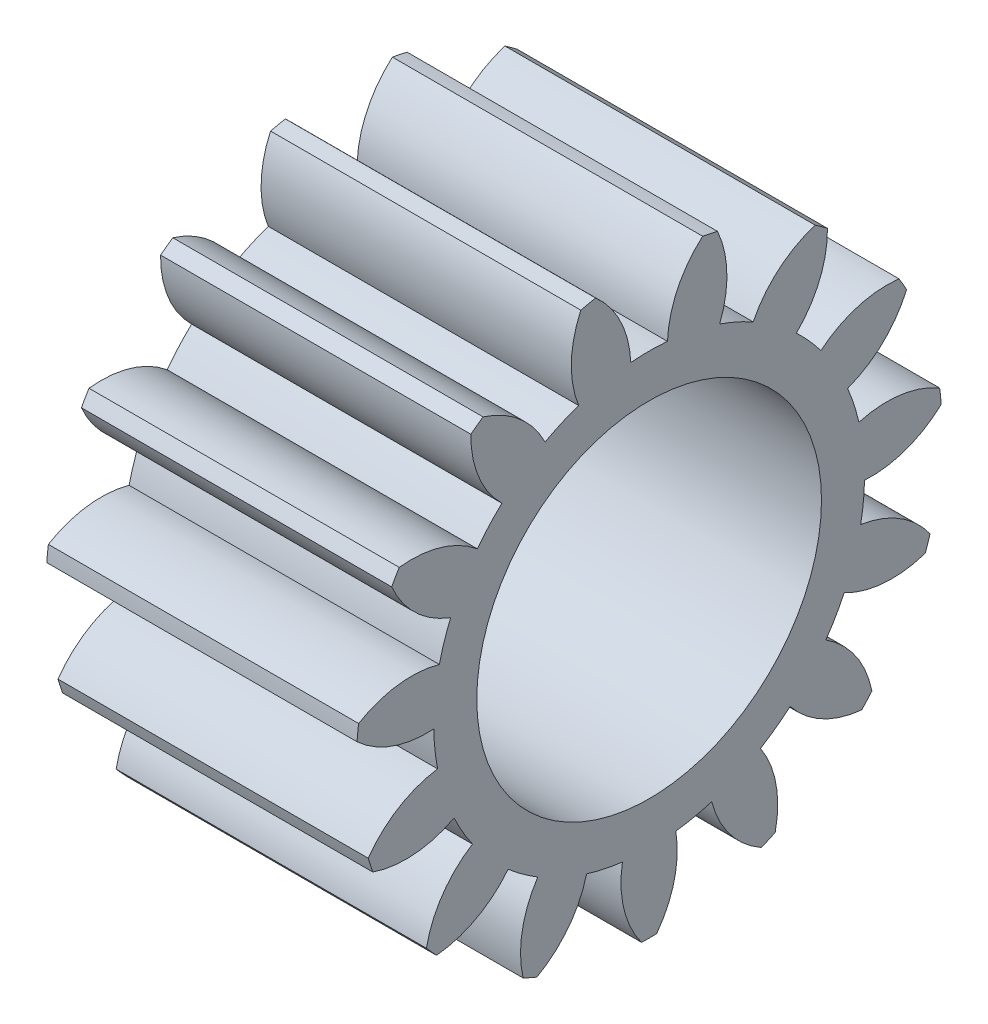
SolidWorks part; units mm, degrees
ref_plane "Plane1" through (0, 0, 0) normal (0, 0, 1) x (1, 0, 0)
ref_plane "Plane2" through (0, 0, 0) normal (0, 1, 0) x (1, 0, 0)
ref_plane "Plane3" through (0, 0, 0) normal (1, 0, 0) x (0, 0, -1)
other "Configuration Table"
sketch "HoldingSke" plane through (0, 0, 0) normal (0, 1, 0) x (1, 0, 0)
  line L0 (0, 0) -> (0.9659, -0.2588)
  line L1 (-15, 0) -> (100, 0) construction
  line L2 (0, 0) -> (-2.1039, 2.3779)
  line L3 (0, 0) -> (-11.863, 4.5341)
  line L4 (0, 0) -> (8.3417, 2.2352)
  line L5 (0, 0) -> (-46.8476, -17.4728)
  line L6 (0, 0) -> (-7.4607, -5.0337)
  line L7 (-2.1039, 2.3779) -> (8.6586, 51.2059)
  line L8 (-76.2, 54.61) -> (-75.2, 54.61)
  line L9 (-71.009, 38.7566) -> (-53.1078, 45.2721)
  line L10 (-76.2, 71.12) -> (104.1128, 71.12)
  line L11 (0, 0) -> (-9, 0)
  line L12 (-76.2, 101.6) -> (-76.162, 101.6)
  line L13 (24.9733, 27.94) -> (52.9518, 28.4284)
  line L14 (24.9733, 27.94) -> (24.9743, 27.94)
  line L15 (24.9733, 27.94) -> (100.4006, 29.5858)
  line L16 (-63.627, -1) -> (-12.827, -1)
  circle A0 centre (0, 0) radius 3
  circle A1 centre (0, 0) radius 6.249
  circle A2 centre (0, 0) radius 37.5
  circle A3 centre (0, 0) radius 3
  dimension "MHD" = 12.498
  dimension "Hub_dia" = 75
  dimension "Bore" = 6
  dimension "MBD" = 6
  dimension "Num_teeth" = 15
  dimension "Pitch" = 1
  dimension "Overall_len" = 50
  dimension "Show_teeth" = 15
  dimension "Thickness" = 9
  dimension "OAL" = 50.0001
  dimension "T_dim" = 1
  dimension "Ap" = 20
  dimension "H" = 19.05
  dimension "Pitch_radius" = 180.3128
  dimension "Width" = 9
  dimension "Backlash" = 0.038
  dimension "Addendum_fac" = 1
  dimension "Dedendum_fac" = 1.25
  dimension "Clearance_fac" = 0.25
  dimension "Dedendum_add" = 0.001
  dimension "Module" = 1
sketch "BasProSke" plane through (0, 0, 0) normal (0, 1, 0) x (1, 0, 0)
  line L0 (-10, 0) -> (60, 0) construction
  line L1 (0, 0) -> (0, 8.5)
  line L2 (0, 0) -> (9, 0)
  line L3 (9, 0) -> (9, 8.5)
  line L4 (9, 8.5) -> (0, 8.5)
  dimension "Thickness" = 9
  dimension "Diameter" = 17
revolve "Base-Revolve" add sketch "BasProSke" angle 360 about L0
sketch "TooCutSke" plane through (0, 0, 0) normal (1, 0, 0) x (0, 0, -1)
  line L1 (0, 0) -> (0, 107) construction
  line L2 (0, 0) -> (-0.8504, 7.4516) construction
  line L3 (0, 0) -> (-3.1044, 14.6049) construction
  line L4 (-0.8504, 7.4516) -> (-1.5522, 7.3025) construction
  arc A0 (0.5316, 6.2263) -> (-0.5316, 6.2263) centre (0, 0) ccw
  arc A1 (1.5766, 8.3784) -> (-1.5766, 8.3784) centre (0, 0) ccw
  circle A2 centre (0, 0) radius 7.5 construction
  circle A3 centre (0, 0) radius 7.0477 construction
  arc A4 (-0.5316, 6.2263) -> (-1.5766, 8.3784) centre (-3.5289, 6.1005) ccw
  arc A5 (1.5766, 8.3784) -> (0.5316, 6.2263) centre (3.5289, 6.1005) ccw
  dimension "Root_dia" = 12.498
  dimension "Overcut_dia" = 17.0508
  dimension "Pitch_dia" = 15
  dimension "Base_dia" = 14.0954
  dimension "Flank_rad" = 3
  dimension "Half_ang" = 12
  dimension "Half_CT" = 0.7175
extrude "ToothCut" cut sketch "TooCutSke" along normal through all
fillet "Breaks" [suppressed] radius 0.02
fillet "RootFillets" [suppressed] radius 0.251
pattern_circular "TeethCuts" count 15 every 24 about axis through (-10, 0, 0) along (1, 0, 0) of "ToothCut", "RootFillets", "Breaks"
sketch "HubNeaOneSke" plane through (0, 0, 0) normal (-1, 0, 0) x (0, 0, 1)
  circle A0 centre (0, 0) radius 6.249
  dimension "Diameter" = 12.498
extrude "HubNearOne" [suppressed] add sketch "HubNeaOneSke" along normal blind 41.0001
sketch "HubNeaBotSke" plane through (0, 0, 0) normal (-1, 0, 0) x (0, 0, 1)
  circle A0 centre (0, 0) radius 6.249
  dimension "Diameter" = 12.498
extrude "HubNearBoth" [suppressed] add sketch "HubNeaBotSke" along normal blind 20.5
ref_plane "FarPln" through (9, 0, 0) normal (1, 0, 0) x (0, 0, -1)
sketch "HubFarSke" plane through (9, 0, 0) normal (1, 0, 0) x (0, 0, -1)
  circle A0 centre (0, 0) radius 6.249
  dimension "Diameter" = 12.498
extrude "HubFar" [suppressed] add sketch "HubFarSke" along normal blind 20.5
sketch "BorSke" plane through (0, 0, 0) normal (1, 0, 0) x (0, 0, -1)
  circle A0 centre (0, 0) radius 3
  dimension "Diameter" = 6
extrude "Bore" cut sketch "BorSke" along normal mid plane 100.0001
sketch "KeySke" plane through (0, 0, 0) normal (1, 0, 0) x (0, 0, -1)
  line L0 (-1, 0) -> (-1, 4)
  line L1 (-1, 4) -> (1, 4)
  line L2 (1, 4) -> (1, 0)
  line L3 (0, 0) -> (0, 34) construction
  line L4 (-1, 0) -> (1, 0)
  dimension "Offset" = 4
  dimension "Width" = 2
extrude "Keyway" [suppressed] cut sketch "KeySke" along normal mid plane 100.0001
pattern_circular "Keyway2" [suppressed] count 2 every 90 about axis through (-10, 0, 0) along (1, 0, 0)
sketch "Sketch1" plane through (9, 0, 0) normal (1, 0, 0) x (0, 0, -1)
  circle A0 centre (0, 0) radius 5
  dimension "D1" = 10
extrude "Cut-Extrude1" cut sketch "Sketch1" against normal up to surface (9 mm away) up to face at (0, 0, -3)
equation "' \"Module@HoldingSke\" = 6.35"
equation "' \"Num_teeth@HoldingSke\" = 12"
equation "' \"Ap@HoldingSke\" =  20"
equation "' \"Ap@HoldingSke\" = 20"
equation "' \"Width@HoldingSke\" = 0.5 * 25.4"
equation "' \"Hub_dia@HoldingSke\"= 1 * 25.4"
equation "' \"Hub_dia@HoldingSke\" = 1 * 25.4"
equation "' \"Overall_len@HoldingSke\" = 1.0 * 25.4"
equation "' \"Bore@HoldingSke\" = 0.75 * 25.4"
equation "' \"T_dim@HoldingSke\" = 0.1 * 25.4"
equation "' \"Width@KeySke\" = 0.25 * 25.4"
equation "' \"Show_teeth@HoldingSke\" = 13"
equation "' \"Backlash@HoldingSke\" = 0.009 * 25.4"
equation "' \"Addendum_fac@HoldingSke\" = 1.0"
equation "' \"Dedendum_fac@HoldingSke\" = 1.25"
equation "' \"Dedendum_add@HoldingSke\" = 0.00005 * 25.4"
equation "' \"Clearance_fac@HoldingSke\" = 0.25"
equation "\"Pitch@HoldingSke\" = 1 / \"Module@HoldingSke\""
equation "\"Overcut_dia@TooCutSke\" = (\"Num_teeth@HoldingSke\" + 2 * \"Addendum_fac@HoldingSke\") / \"Pitch@HoldingSke\" + 0.002 * 25.4"
equation "\"Pitch_dia@TooCutSke\" = \"Num_teeth@HoldingSke\" / \"Pitch@HoldingSke\""
equation "\"Base_dia@TooCutSke\" = \"Num_teeth@HoldingSke\" / \"Pitch@HoldingSke\" * cos((\"Ap@HoldingSke\"  * 3.14159265 / 180))"
equation "\"Root_dia@TooCutSke\" = (\"Num_teeth@HoldingSke\" + 2) / \"Pitch@HoldingSke\" - 2 * (\"Addendum_fac@HoldingSke\" + \"Dedendum_fac@HoldingSke\") / \"Pitch@HoldingSke\" - \"Dedendum_add@HoldingSke\" * 2"
equation "\"Half_ang@TooCutSke\" = 180 / \"Num_teeth@HoldingSke\""
equation "\"Half_CT@TooCutSke\" = \"Num_teeth@HoldingSke\" / \"Pitch@HoldingSke\" * sin((3.14159265 / 2 / \"Num_teeth@HoldingSke\")) / 2 - 7 * \"Backlash@HoldingSke\" / 4"
equation "\"Flank_rad@TooCutSke\" = \"Num_teeth@HoldingSke\" / \"Pitch@HoldingSke\" / 5"
equation "\"Radius@RootFillets\" = \"Clearance_fac@HoldingSke\" / \"Pitch@HoldingSke\" + \"Dedendum_add@HoldingSke\""
equation "\"Break_rad@Breaks\" = 0.02 / \"Pitch@HoldingSke\""
equation "\"Thickness@HoldingSke\" = \"Width@HoldingSke\""
equation "\"OAL@HoldingSke\" = \"Thickness@HoldingSke\""
equation "\"MHD@HoldingSke\" = (\"Num_teeth@HoldingSke\" + 2) / \"Pitch@HoldingSke\" - 2 * (\"Addendum_fac@HoldingSke\" + \"Dedendum_fac@HoldingSke\")  / \"Pitch@HoldingSke\" - \"Dedendum_add@HoldingSke\" * 2"
equation "\"MBD@HoldingSke\" = (\"Num_teeth@HoldingSke\" + 2) / \"Pitch@HoldingSke\" - 2 * (\"Addendum_fac@HoldingSke\" + \"Dedendum_fac@HoldingSke\")  / \"Pitch@HoldingSke\" - \"Dedendum_add@HoldingSke\" * 2 - 0.002 * 25.4"
equation "\"MHD@HoldingSke\" = ((sgn( \"MHD@HoldingSke\" - \"Hub_dia@HoldingSke\" )-1)*( \"MHD@HoldingSke\" - \"Hub_dia@HoldingSke\" ))/-2+ \"Hub_dia@HoldingSke\""
equation "\"MBD@HoldingSke\" = ((sgn( \"MBD@HoldingSke\" - \"Bore@HoldingSke\" )-1)*( \"MBD@HoldingSke\" - \"Bore@HoldingSke\" ))/-2+ \"Bore@HoldingSke\""
equation "\"OAL@HoldingSke\" = ((sgn( \"OAL@HoldingSke\" - \"Overall_len@HoldingSke\" )+1)*( \"OAL@HoldingSke\" - \"Overall_len@HoldingSke\" ))/2 + \"Overall_len@HoldingSke\" + 0.000002 * 25.4"
equation "\"Num_teeth@TeethCuts\" = int( \"Show_teeth@HoldingSke\" ) + 1"
equation "\"Num_teeth@TeethCuts\" = ((sgn( \"Num_teeth@TeethCuts\" - \"Num_teeth@HoldingSke\" )-1)*( \"Num_teeth@TeethCuts\" - \"Num_teeth@HoldingSke\" ))/-2+ \"Num_teeth@HoldingSke\""
equation "\"Num_teeth@TeethCuts\" = ((sgn( \"Num_teeth@TeethCuts\" - 2.0)+1)*( \"Num_teeth@TeethCuts\" - 2.0))/2 +2.0"
equation "\"Angle@TeethCuts\" = 360.0 / \"Num_teeth@HoldingSke\""
equation "\"Diameter@BasProSke\" = (\"Num_teeth@HoldingSke\" + 2 * \"Addendum_fac@HoldingSke\") / \"Pitch@HoldingSke\""
equation "\"Thickness@BasProSke\"  = \"Thickness@HoldingSke\""
equation "' \"Fillet_rad@BasProSke\" =  \"Thickness@HoldingSke\" * 0.05"
equation "' \"Fillet_rad@BasProSke\" = \"Thickness@HoldingSke\" * 0.05"
equation "\"MHD@HoldingSke\" = ((sgn( \"MHD@HoldingSke\" - \"Root_dia@TooCutSke\" )-1)*( \"MHD@HoldingSke\" - \"Root_dia@TooCutSke\" ))/-2+ \"Root_dia@TooCutSke\""
equation "\"Diameter@HubNeaOneSke\" = \"MHD@HoldingSke\""
equation "\"Length@HubNearOne\" = \"OAL@HoldingSke\" - \"Thickness@BasProSke\""
equation "\"Diameter@HubNeaBotSke\" = \"MHD@HoldingSke\""
equation "\"Length@HubNearBoth\" = ( \"OAL@HoldingSke\" - \"Thickness@BasProSke\" ) / 2.0"
equation "\"Thickness@FarPln\" = \"Thickness@BasProSke\""
equation "\"Diameter@HubFarSke\" = \"MHD@HoldingSke\""
equation "\"Length@HubFar\" = ( \"OAL@HoldingSke\" - \"Thickness@BasProSke\" ) / 2.0"
equation "\"Diameter@BorSke\" = \"MBD@HoldingSke\""
equation "\"D1@Bore\" = \"OAL@HoldingSke\" * 2.0"
equation "\"D1@Keyway\" = \"OAL@HoldingSke\" * 2.0"
equation "\"Offset@KeySke\" = \"T_dim@HoldingSke\" + \"MBD@HoldingSke\" / 2.0"
